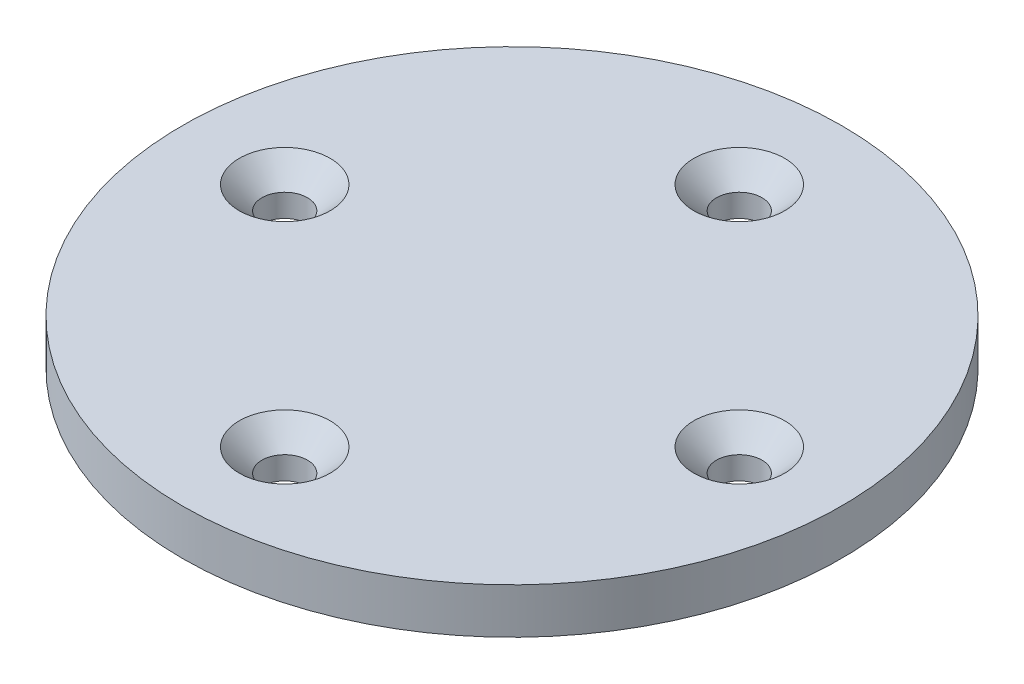
SolidWorks part; units mm, degrees
ref_plane "Front Plane" through (0, 0, 0) normal (0, 0, 1) x (1, 0, 0)
ref_plane "Top Plane" through (0, 0, 0) normal (0, 1, 0) x (1, 0, 0)
ref_plane "Right Plane" through (0, 0, 0) normal (1, 0, 0) x (0, 0, -1)
sketch "Sketch1" plane through (0, 0, 0) normal (0, 1, 0) x (1, 0, 0)
  circle A0 centre (0, 0) radius 14.5
  dimension "D1" = 29
extrude "Boss-Extrude1" add sketch "Sketch1" along normal blind 2
sketch "Sketch2" plane through (0, 2, 0) normal (0, 1, 0) x (1, 0, 0)
  circle A0 centre (0, 0) radius 10 construction
  circle A1 centre (0, 10) radius 1.2205
  circle A2 centre (10, 0) radius 1.2205
  circle A3 centre (0, -10) radius 1.2205
  circle A4 centre (-10, 0) radius 1.2205
  point P2 (0, 10)
  point P8 (10, 0)
  point P10 (0, -10)
  point P12 (-10, 0)
  point P14 (0, 0)
  dimension "D1" = 20
  dimension "D2" = 4
hole_wizard "Ø2.0mm Dowel Hole1" positions "Sketch2" profile "Sketch3" hole size "Ø2.0" standard "ANSI Metric"
sketch "Sketch3" plane through (-10, 2, 0) normal (1, 0, 0) x (0, 0, 1)
  line L0 (0, 0) -> (0, 43.5309)
  line L1 (0, 43.5309) -> (1, 42.93)
  line L2 (1, 42.93) -> (1, 0)
  line L5 (1, 0) -> (0, 0)
  line L10 (0, 43.5309) -> (-1, 42.93) construction
  line L11 (0, -6.35) -> (0, 107.95) construction
  dimension "Hole Dia." = 2
  dimension "Hole Depth" = 42.93
  dimension "Drill Angle" = 118
chamfer "Chamfer1" distance 1 angle 45 4 edges at (10, 2, 1) (0, 2, 11) (0, 2, -9) (-10, 2, 1)
